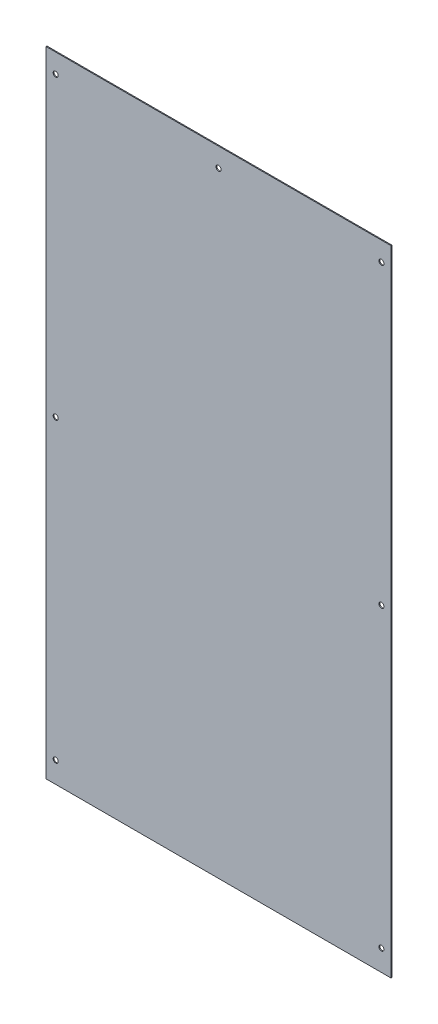
SolidWorks part; units mm, degrees
material "1023 Carbon Steel Sheet (SS)"
ref_plane "Front Plane" through (0, 0, 0) normal (0, 0, 1) x (1, 0, 0)
ref_plane "Top Plane" through (0, 0, 0) normal (0, 1, 0) x (1, 0, 0)
ref_plane "Right Plane" through (0, 0, 0) normal (1, 0, 0) x (0, 0, -1)
sketch "Sketch1" plane through (0, 0, 0) normal (0, 0, 1) x (1, 0, 0)
  line L1 (0, 0) -> (457.2, 0)
  line L2 (0, 0) -> (0, 840.74)
  line L3 (0, 840.74) -> (457.2, 840.74)
  line L4 (457.2, 0) -> (457.2, 840.74)
  line L5 (12.7, 815.34) -> (444.5, 815.34) construction
  line L6 (12.7, 815.34) -> (12.7, 25.4) construction
  line L7 (12.7, 25.4) -> (444.5, 25.4) construction
  line L8 (444.5, 815.34) -> (444.5, 25.4) construction
  dimension "D1" = 840.74
  dimension "D2" = 457.2
  dimension "D3" = 12.7
  dimension "D4" = 12.7
  dimension "D5" = 25.4
  dimension "D6" = 25.4
extrude "Boss-Extrude1" add sketch "Sketch1" along normal blind 1.2192
sketch "Sketch2" plane through (0, 0, 1.2192) normal (0, 0, 1) x (1, 0, 0)
  line L0 (457.2, 840.74) -> (0, 840.74) construction
  line L1 (12.7, 815.34) -> (444.5, 815.34) construction
  line L2 (12.7, 815.34) -> (12.7, 27.94) construction
  line L3 (12.7, 27.94) -> (444.5, 27.94) construction
  line L4 (444.5, 815.34) -> (444.5, 27.94) construction
  line L5 (0, 0) -> (457.2, 0) construction
  line L6 (0, 840.74) -> (0, 0) construction
  line L7 (457.2, 0) -> (457.2, 840.74) construction
  point P4 (228.6, 840.74)
  point P14 (228.6, 815.34)
  point P15 (12.7, 815.34)
  point P16 (444.5, 421.64)
  point P17 (444.5, 815.34)
  point P18 (228.6, 27.94)
  point P19 (444.5, 27.94)
  point P20 (12.7, 421.64)
  point P21 (12.7, 27.94)
  dimension "D1" = 25.4
  dimension "D2" = 393.7
  dimension "D3" = 12.7
  dimension "D4" = 12.7
hole_wizard "1/4 Clearance Hole1" positions "Sketch4" profile "Sketch3" hole size "1/4" standard "ANSI Inch" end condition through all
sketch "Sketch4" plane through (0, 0, 1.2192) normal (0, 0, 1) x (1, 0, 0)
  point P0 (12.7, 815.34)
  point P3 (228.6, 815.34)
  point P6 (444.5, 815.34)
  point P9 (444.5, 421.64)
  point P12 (12.7, 421.64)
  point P15 (12.7, 27.94)
  point P18 (444.5, 27.94)
sketch "Sketch3" plane through (12.7, 815.34, 1.2192) normal (1, 0, 0) x (0, -1, 0)
  line L0 (0, 0) -> (0, 1.2192)
  line L1 (0, 1.2192) -> (3.3782, 1.2192)
  line L2 (3.3782, 1.2192) -> (3.3782, 0)
  line L5 (3.3782, 0) -> (0, 0)
  line L11 (0, -6.35) -> (0, 107.95) construction
  dimension "Thru Hole Dia." = 6.7564
  dimension "Thru Hole Depth" = 1.2192
equation "\"d1\"=0.5"
equation "\"d2\"=1"
